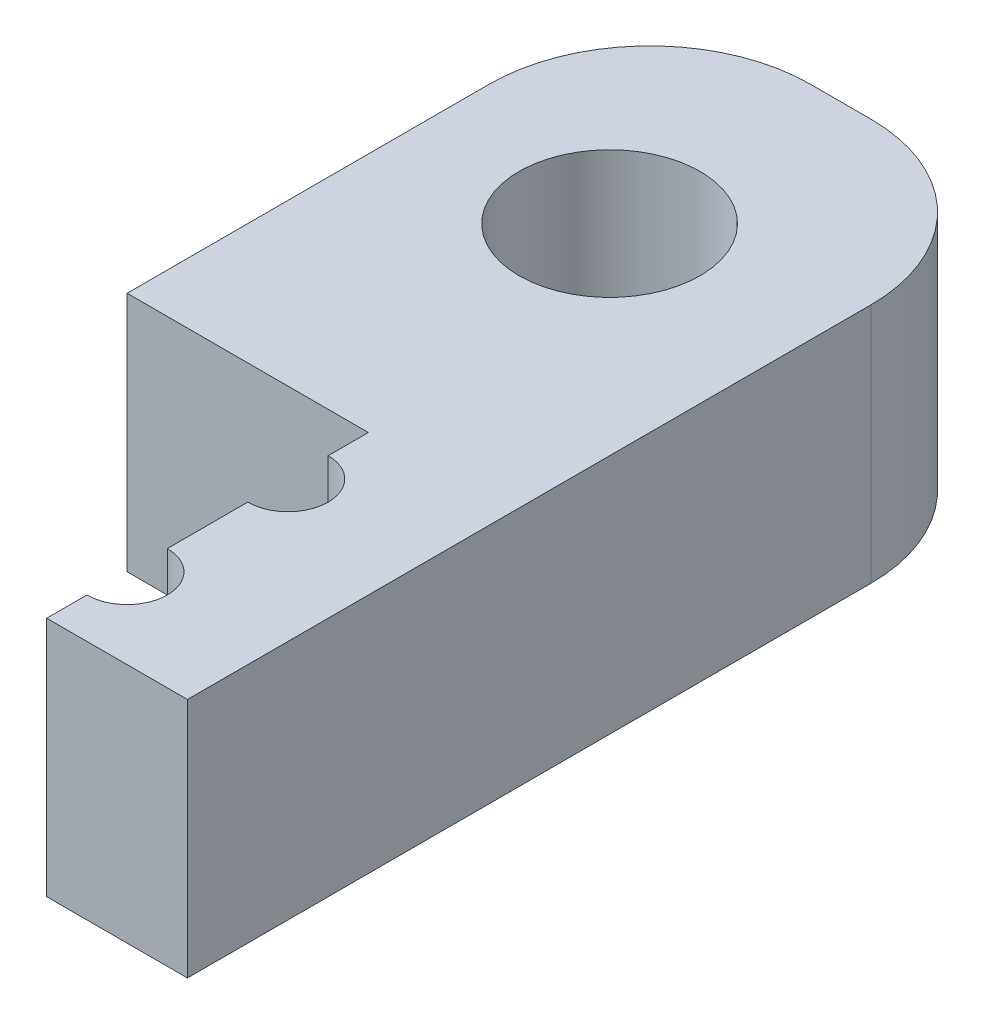
SolidWorks part; units mm, degrees
ref_plane "Front Plane" through (0, 0, 0) normal (0, 0, 1) x (1, 0, 0)
ref_plane "Top Plane" through (0, 0, 0) normal (0, 1, 0) x (1, 0, 0)
ref_plane "Right Plane" through (0, 0, 0) normal (1, 0, 0) x (0, 0, -1)
sketch "Sketch1" plane through (0, 0, 0) normal (0, 1, 0) x (1, 0, 0)
  line L3 (0, 13) -> (9.5, 13)
  line L4 (9.5, -8) -> (9.5, 13)
  line L5 (0, 0) -> (6, 0)
  line L6 (6, 0) -> (6, -8)
  line L7 (6, -8) -> (9.5, -8)
  line L8 (0, 0) -> (0, 13)
  dimension "D1" = 13
  dimension "D2" = 0
  dimension "D3" = 8
  dimension "D4" = 6
  dimension "D5" = 3.5
extrude "Boss-Extrude1" add sketch "Sketch1" along normal blind 6
sketch "Sketch2" plane through (0, 6, 0) normal (0, 1, 0) x (1, 0, 0)
  line L2 (0, 0) -> (6, 0) construction
  line L4 (6, 0) -> (6, -8) construction
  line L7 (0, 13) -> (0, 0) construction
  line L8 (6, -8) -> (9.5, -8) construction
  circle A0 centre (6, -2) radius 1
  circle A1 centre (4.5, 7.5) radius 2.25
  circle A2 centre (6, -6) radius 1
  dimension "D3" = 2
  dimension "D7" = 4.5
  dimension "D2" = 2
  dimension "D5" = 2
  dimension "D1" = 7.5
  dimension "D4" = 2
  dimension "D8" = 4.5
extrude "Cut-Extrude1" cut sketch "Sketch2" against normal through all
fillet "Fillet1" radius 4 2 edges at (9.5, 3, -13) (0, 3, -13)
